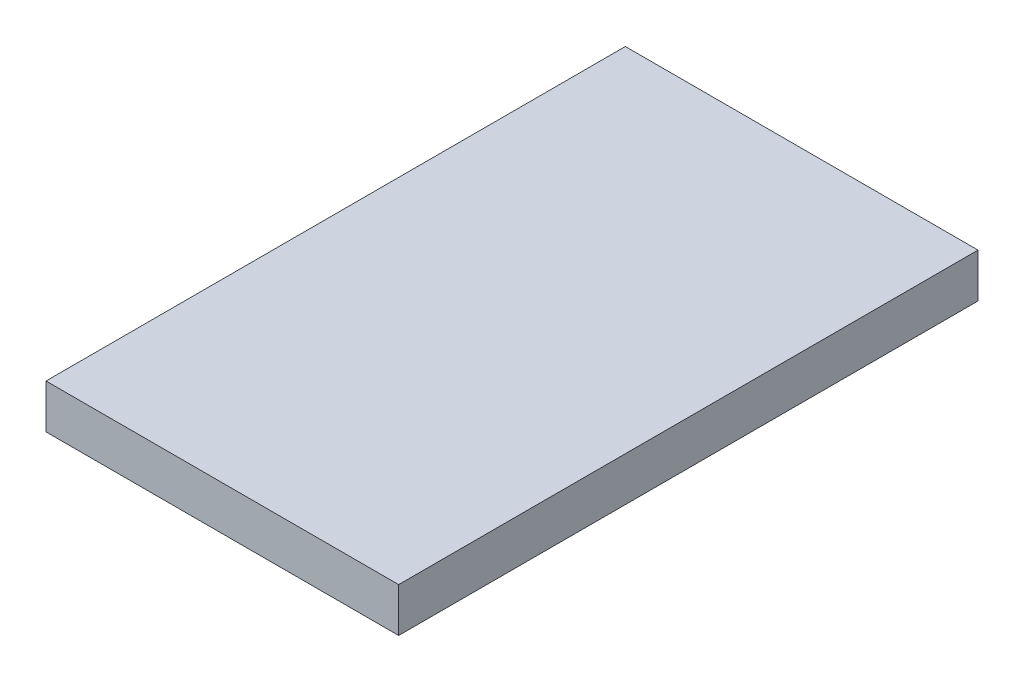
SolidWorks part; units mm, degrees
ref_plane "前视基准面" through (0, 0, 0) normal (0, 0, 1) x (1, 0, 0)
ref_plane "上视基准面" through (0, 0, 0) normal (0, 1, 0) x (1, 0, 0)
ref_plane "右视基准面" through (0, 0, 0) normal (1, 0, 0) x (0, 0, -1)
sketch "草图1" plane through (0, 0, 0) normal (0, 0, 1) x (1, 0, 0)
  line L1 (-28, 3.5) -> (28, 3.5)
  line L2 (-28, 3.5) -> (-28, -3.5)
  line L3 (-28, -3.5) -> (28, -3.5)
  line L4 (28, 3.5) -> (28, -3.5)
  line L5 (-28, 3.5) -> (28, -3.5) construction
  line L6 (-28, -3.5) -> (28, 3.5) construction
  point P0 (0, 0)
  dimension "D1" = 56
  dimension "D2" = 7
extrude "凸台-拉伸1" add sketch "草图1" along normal blind 92
